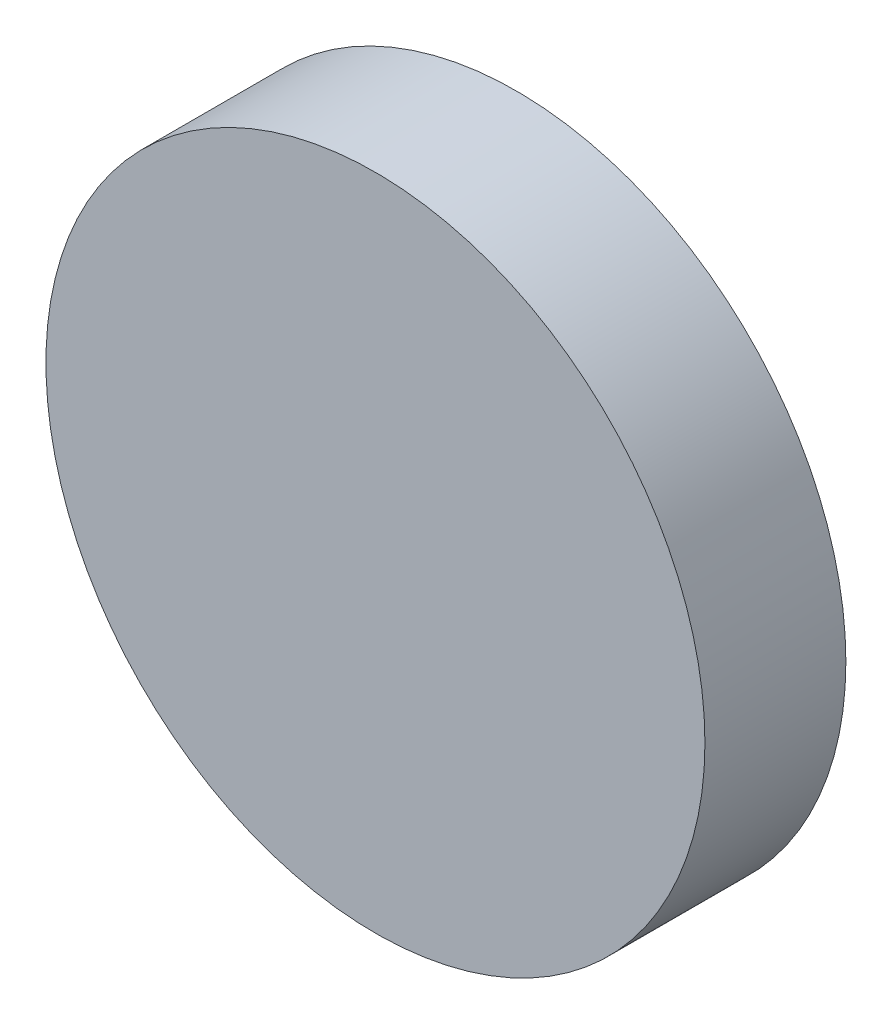
SolidWorks part; units mm, degrees
ref_plane "Front Plane" through (0, 0, 0) normal (0, 0, 1) x (1, 0, 0)
ref_plane "Top Plane" through (0, 0, 0) normal (0, 1, 0) x (1, 0, 0)
ref_plane "Right Plane" through (0, 0, 0) normal (1, 0, 0) x (0, 0, -1)
sketch "Sketch1" plane through (-8.8505, 5.8745, 0) normal (0, 0, 1) x (1, 0, 0)
  circle A0 centre (-8.9682, 7.9455) radius 25.7159
  arc A1 (10.8563, 18.4871) -> (-9.6615, 27.5003) centre (0, 21.6338) ccw
extrude "Boss-Extrude1" add sketch "Sketch1" along normal blind 11
